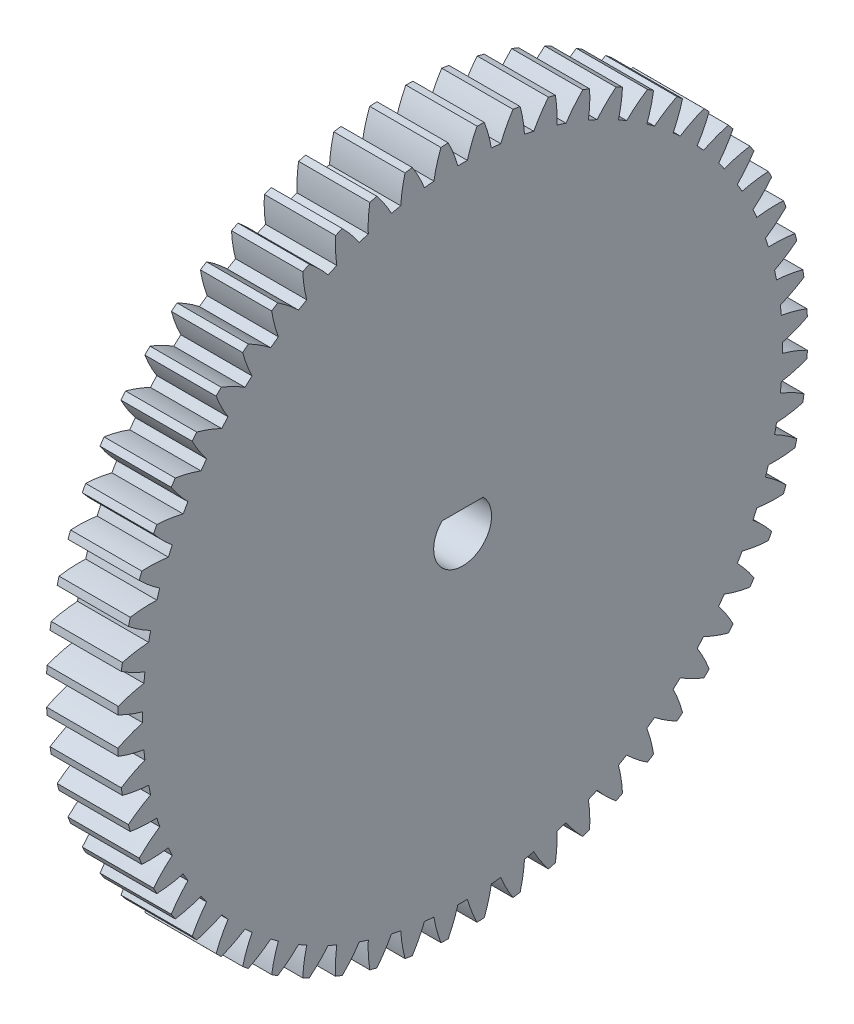
SolidWorks part; units mm, degrees
ref_plane "Plane1" through (0, 0, 0) normal (0, 0, 1) x (1, 0, 0)
ref_plane "Plane2" through (0, 0, 0) normal (0, 1, 0) x (1, 0, 0)
ref_plane "Plane3" through (0, 0, 0) normal (1, 0, 0) x (0, 0, -1)
sketch "HoldingSke" plane through (0, 0, 0) normal (0, 1, 0) x (1, 0, 0)
  line L0 (0, 0) -> (0.4, -0.6928)
  line L1 (-15, 0) -> (100, 0) construction
  line L2 (0, 0) -> (-2.1039, 2.3779)
  line L3 (0, 0) -> (-11.863, 4.5341)
  line L4 (0, 0) -> (4.318, 7.479)
  line L5 (0, 0) -> (-46.8476, -17.4728)
  line L6 (0, 0) -> (-6.6317, -4.4744)
  line L7 (-2.1039, 2.3779) -> (8.6586, 51.2059)
  line L8 (-76.2, 54.61) -> (-75.2, 54.61)
  line L9 (-71.009, 38.7566) -> (-53.1078, 45.2721)
  line L10 (-76.2, 71.12) -> (104.1128, 71.12)
  line L11 (0, 0) -> (-8, 0)
  line L12 (-76.2, 101.6) -> (-76.155, 101.6)
  line L13 (24.9733, 27.94) -> (52.9518, 28.4284)
  line L14 (24.9733, 27.94) -> (24.9743, 27.94)
  line L15 (24.9733, 27.94) -> (100.4006, 29.5858)
  line L16 (-63.627, -1.25) -> (-12.827, -1.25)
  circle A0 centre (0, 0) radius 3.5
  circle A1 centre (0, 0) radius 35.9365
  circle A2 centre (0, 0) radius 37.5
  circle A3 centre (0, 0) radius 3.5
  dimension "MHD" = 71.873
  dimension "Hub_dia" = 75
  dimension "Bore" = 7
  dimension "MBD" = 7
  dimension "Num_teeth" = 60
  dimension "Pitch" = 0.8
  dimension "Overall_len" = 50
  dimension "Show_teeth" = 60
  dimension "Thickness" = 8
  dimension "OAL" = 50.0001
  dimension "T_dim" = 1
  dimension "Ap" = 20
  dimension "H" = 19.05
  dimension "Pitch_radius" = 180.3128
  dimension "Width" = 8
  dimension "Backlash" = 0.045
  dimension "Addendum_fac" = 1
  dimension "Dedendum_fac" = 1.25
  dimension "Clearance_fac" = 0.25
  dimension "Dedendum_add" = 0.001
  dimension "Module" = 1.25
sketch "BasProSke" plane through (0, 0, 0) normal (0, 1, 0) x (1, 0, 0)
  line L0 (-10, 0) -> (60, 0) construction
  line L1 (0, 0) -> (0, 38.75)
  line L2 (0, 0) -> (8, 0)
  line L3 (8, 0) -> (8, 38.75)
  line L4 (8, 38.75) -> (0, 38.75)
  dimension "Thickness" = 8
  dimension "Diameter" = 77.5
revolve "Base-Revolve" add sketch "BasProSke" angle 360 about L0
sketch "TooCutSke" plane through (0, 0, 0) normal (1, 0, 0) x (0, 0, -1)
  line L1 (0, 0) -> (0, 107) construction
  line L2 (0, 0) -> (-1.0604, 37.485) construction
  line L3 (0, 0) -> (-3.9241, 74.8755) construction
  line L4 (-1.0604, 37.485) -> (-1.962, 37.4378) construction
  arc A0 (0.5336, 35.9325) -> (-0.5336, 35.9325) centre (0, 0) ccw
  arc A1 (1.6331, 38.741) -> (-1.6331, 38.741) centre (0, 0) ccw
  circle A2 centre (0, 0) radius 37.5 construction
  circle A3 centre (0, 0) radius 35.2385 construction
  arc A4 (-0.5336, 35.9325) -> (-1.6331, 38.741) centre (-14.9802, 31.8958) ccw
  arc A5 (1.6331, 38.741) -> (0.5336, 35.9325) centre (14.9802, 31.8958) ccw
  dimension "Root_dia" = 71.873
  dimension "Overcut_dia" = 77.5508
  dimension "Pitch_dia" = 75
  dimension "Base_dia" = 70.4769
  dimension "Flank_rad" = 15
  dimension "Half_ang" = 3
  dimension "Half_CT" = 0.9029
extrude "ToothCut" cut sketch "TooCutSke" along normal through all
fillet "Breaks" [suppressed] radius 0.025
fillet "RootFillets" [suppressed] radius 0.3135
pattern_circular "TeethCuts" count 60 every 6 about axis through (-10, 0, 0) along (1, 0, 0) of "ToothCut", "RootFillets", "Breaks"
sketch "HubNeaOneSke" plane through (0, 0, 0) normal (-1, 0, 0) x (0, 0, 1)
  circle A0 centre (0, 0) radius 35.9365
  dimension "Diameter" = 71.873
extrude "HubNearOne" [suppressed] add sketch "HubNeaOneSke" along normal blind 42.0001
sketch "HubNeaBotSke" plane through (0, 0, 0) normal (-1, 0, 0) x (0, 0, 1)
  circle A0 centre (0, 0) radius 35.9365
  dimension "Diameter" = 71.873
extrude "HubNearBoth" [suppressed] add sketch "HubNeaBotSke" along normal blind 21
ref_plane "FarPln" through (8, 0, 0) normal (1, 0, 0) x (0, 0, -1)
sketch "HubFarSke" plane through (8, 0, 0) normal (1, 0, 0) x (0, 0, -1)
  circle A0 centre (0, 0) radius 35.9365
  dimension "Diameter" = 71.873
extrude "HubFar" [suppressed] add sketch "HubFarSke" along normal blind 21
sketch "BorSke" plane through (0, 0, 0) normal (1, 0, 0) x (0, 0, -1)
  circle A0 centre (0, 0) radius 3.5
  dimension "Diameter" = 7
extrude "Bore" cut sketch "BorSke" along normal mid plane 100.0001
sketch "KeySke" plane through (0, 0, 0) normal (1, 0, 0) x (0, 0, -1)
  line L0 (-1, 0) -> (-1, 4.5)
  line L1 (-1, 4.5) -> (1, 4.5)
  line L2 (1, 4.5) -> (1, 0)
  line L3 (0, 0) -> (0, 34) construction
  line L4 (-1, 0) -> (1, 0)
  dimension "Offset" = 4.5
  dimension "Width" = 2
extrude "Keyway" [suppressed] cut sketch "KeySke" along normal mid plane 100.0001
pattern_circular "Keyway2" [suppressed] count 2 every 90 about axis through (-10, 0, 0) along (1, 0, 0)
sketch "Sketch1" plane through (8, 0, 0) normal (1, 0, 0) x (0, 0, -1)
  line L0 (-2.65, 2.2864) -> (2.65, 2.2864)
  circle A1 centre (0, 0) radius 3.5 construction
  circle A2 centre (0, 0) radius 3.5
  circle A3 centre (0, 0) radius 3.25
  dimension "D1" = 5.3
  dimension "D2" = 6.5
extrude "Boss-Extrude1" add sketch "Sketch1" against normal up to surface (8 mm away) contours L0 A3 | A3 L0 A2 | A3 L0 A2
equation "' \"Module@HoldingSke\" = 6.35"
equation "' \"Num_teeth@HoldingSke\" = 12"
equation "' \"Ap@HoldingSke\" =  20"
equation "' \"Ap@HoldingSke\" = 20"
equation "' \"Width@HoldingSke\" = 0.5 * 25.4"
equation "' \"Hub_dia@HoldingSke\"= 1 * 25.4"
equation "' \"Hub_dia@HoldingSke\" = 1 * 25.4"
equation "' \"Overall_len@HoldingSke\" = 1.0 * 25.4"
equation "' \"Bore@HoldingSke\" = 0.75 * 25.4"
equation "' \"T_dim@HoldingSke\" = 0.1 * 25.4"
equation "' \"Width@KeySke\" = 0.25 * 25.4"
equation "' \"Show_teeth@HoldingSke\" = 13"
equation "' \"Backlash@HoldingSke\" = 0.009 * 25.4"
equation "' \"Addendum_fac@HoldingSke\" = 1.0"
equation "' \"Dedendum_fac@HoldingSke\" = 1.25"
equation "' \"Dedendum_add@HoldingSke\" = 0.00005 * 25.4"
equation "' \"Clearance_fac@HoldingSke\" = 0.25"
equation "\"Pitch@HoldingSke\" = 1 / \"Module@HoldingSke\""
equation "\"Overcut_dia@TooCutSke\" = (\"Num_teeth@HoldingSke\" + 2 * \"Addendum_fac@HoldingSke\") / \"Pitch@HoldingSke\" + 0.002 * 25.4"
equation "\"Pitch_dia@TooCutSke\" = \"Num_teeth@HoldingSke\" / \"Pitch@HoldingSke\""
equation "\"Base_dia@TooCutSke\" = \"Num_teeth@HoldingSke\" / \"Pitch@HoldingSke\" * cos((\"Ap@HoldingSke\"  * 3.14159265 / 180))"
equation "\"Root_dia@TooCutSke\" = (\"Num_teeth@HoldingSke\" + 2) / \"Pitch@HoldingSke\" - 2 * (\"Addendum_fac@HoldingSke\" + \"Dedendum_fac@HoldingSke\") / \"Pitch@HoldingSke\" - \"Dedendum_add@HoldingSke\" * 2"
equation "\"Half_ang@TooCutSke\" = 180 / \"Num_teeth@HoldingSke\""
equation "\"Half_CT@TooCutSke\" = \"Num_teeth@HoldingSke\" / \"Pitch@HoldingSke\" * sin((3.14159265 / 2 / \"Num_teeth@HoldingSke\")) / 2 - 7 * \"Backlash@HoldingSke\" / 4"
equation "\"Flank_rad@TooCutSke\" = \"Num_teeth@HoldingSke\" / \"Pitch@HoldingSke\" / 5"
equation "\"Radius@RootFillets\" = \"Clearance_fac@HoldingSke\" / \"Pitch@HoldingSke\" + \"Dedendum_add@HoldingSke\""
equation "\"Break_rad@Breaks\" = 0.02 / \"Pitch@HoldingSke\""
equation "\"Thickness@HoldingSke\" = \"Width@HoldingSke\""
equation "\"OAL@HoldingSke\" = \"Thickness@HoldingSke\""
equation "\"MHD@HoldingSke\" = (\"Num_teeth@HoldingSke\" + 2) / \"Pitch@HoldingSke\" - 2 * (\"Addendum_fac@HoldingSke\" + \"Dedendum_fac@HoldingSke\")  / \"Pitch@HoldingSke\" - \"Dedendum_add@HoldingSke\" * 2"
equation "\"MBD@HoldingSke\" = (\"Num_teeth@HoldingSke\" + 2) / \"Pitch@HoldingSke\" - 2 * (\"Addendum_fac@HoldingSke\" + \"Dedendum_fac@HoldingSke\")  / \"Pitch@HoldingSke\" - \"Dedendum_add@HoldingSke\" * 2 - 0.002 * 25.4"
equation "\"MHD@HoldingSke\" = ((sgn( \"MHD@HoldingSke\" - \"Hub_dia@HoldingSke\" )-1)*( \"MHD@HoldingSke\" - \"Hub_dia@HoldingSke\" ))/-2+ \"Hub_dia@HoldingSke\""
equation "\"MBD@HoldingSke\" = ((sgn( \"MBD@HoldingSke\" - \"Bore@HoldingSke\" )-1)*( \"MBD@HoldingSke\" - \"Bore@HoldingSke\" ))/-2+ \"Bore@HoldingSke\""
equation "\"OAL@HoldingSke\" = ((sgn( \"OAL@HoldingSke\" - \"Overall_len@HoldingSke\" )+1)*( \"OAL@HoldingSke\" - \"Overall_len@HoldingSke\" ))/2 + \"Overall_len@HoldingSke\" + 0.000002 * 25.4"
equation "\"Num_teeth@TeethCuts\" = int( \"Show_teeth@HoldingSke\" ) + 1"
equation "\"Num_teeth@TeethCuts\" = ((sgn( \"Num_teeth@TeethCuts\" - \"Num_teeth@HoldingSke\" )-1)*( \"Num_teeth@TeethCuts\" - \"Num_teeth@HoldingSke\" ))/-2+ \"Num_teeth@HoldingSke\""
equation "\"Num_teeth@TeethCuts\" = ((sgn( \"Num_teeth@TeethCuts\" - 2.0)+1)*( \"Num_teeth@TeethCuts\" - 2.0))/2 +2.0"
equation "\"Angle@TeethCuts\" = 360.0 / \"Num_teeth@HoldingSke\""
equation "\"Diameter@BasProSke\" = (\"Num_teeth@HoldingSke\" + 2 * \"Addendum_fac@HoldingSke\") / \"Pitch@HoldingSke\""
equation "\"Thickness@BasProSke\"  = \"Thickness@HoldingSke\""
equation "' \"Fillet_rad@BasProSke\" =  \"Thickness@HoldingSke\" * 0.05"
equation "' \"Fillet_rad@BasProSke\" = \"Thickness@HoldingSke\" * 0.05"
equation "\"MHD@HoldingSke\" = ((sgn( \"MHD@HoldingSke\" - \"Root_dia@TooCutSke\" )-1)*( \"MHD@HoldingSke\" - \"Root_dia@TooCutSke\" ))/-2+ \"Root_dia@TooCutSke\""
equation "\"Diameter@HubNeaOneSke\" = \"MHD@HoldingSke\""
equation "\"Length@HubNearOne\" = \"OAL@HoldingSke\" - \"Thickness@BasProSke\""
equation "\"Diameter@HubNeaBotSke\" = \"MHD@HoldingSke\""
equation "\"Length@HubNearBoth\" = ( \"OAL@HoldingSke\" - \"Thickness@BasProSke\" ) / 2.0"
equation "\"Thickness@FarPln\" = \"Thickness@BasProSke\""
equation "\"Diameter@HubFarSke\" = \"MHD@HoldingSke\""
equation "\"Length@HubFar\" = ( \"OAL@HoldingSke\" - \"Thickness@BasProSke\" ) / 2.0"
equation "\"Diameter@BorSke\" = \"MBD@HoldingSke\""
equation "\"D1@Bore\" = \"OAL@HoldingSke\" * 2.0"
equation "\"D1@Keyway\" = \"OAL@HoldingSke\" * 2.0"
equation "\"Offset@KeySke\" = \"T_dim@HoldingSke\" + \"MBD@HoldingSke\" / 2.0"
